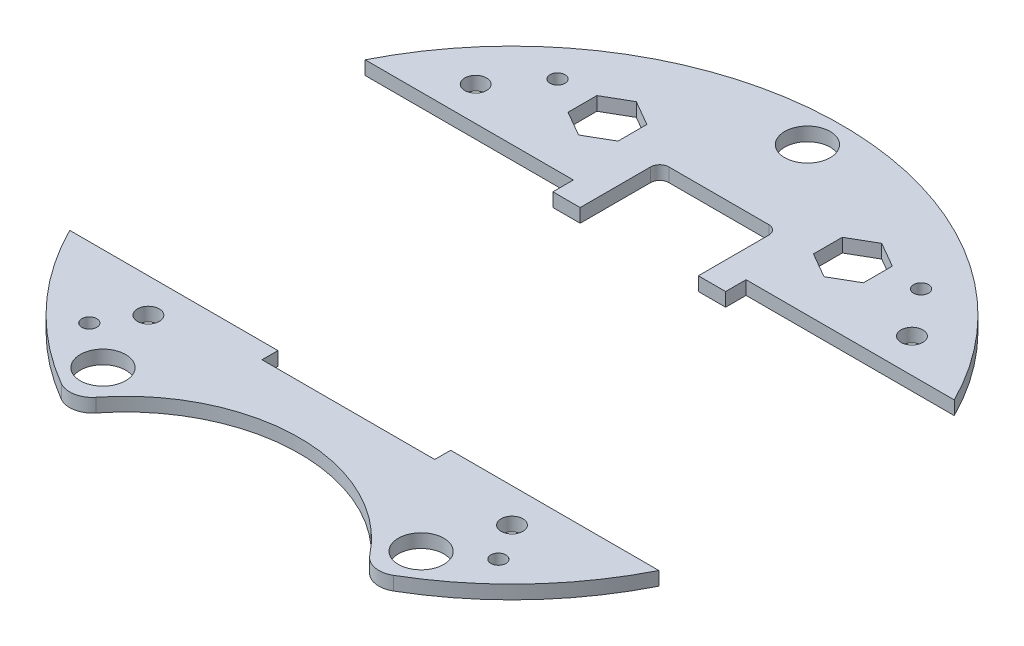
SolidWorks part; units mm, degrees
material "Acrylic (Medium-high impact)"
ref_plane "Front Plane" through (0, 0, 0) normal (0, 0, 1) x (1, 0, 0)
ref_plane "Top Plane" through (0, 0, 0) normal (0, 1, 0) x (1, 0, 0)
ref_plane "Right Plane" through (0, 0, 0) normal (1, 0, 0) x (0, 0, -1)
sketch "Sketch1" plane through (0, 0, 0) normal (0, 1, 0) x (1, 0, 0)
  line L0 (0, -85) -> (-32.4891, -64.8129) construction
  line L1 (0, -85) -> (0, 0) construction
  arc A0 (36.5434, -62.6165) -> (-36.5434, -62.6165) centre (0, 0) ccw
  arc A1 (30.0898, -61.3851) -> (-30.0898, -61.3851) centre (0, -85) ccw
  arc A2 (-30.0898, -61.3851) -> (-36.5434, -62.6165) centre (-34.0231, -58.2982) cw
  arc A3 (36.5434, -62.6165) -> (30.0898, -61.3851) centre (34.0231, -58.2982) cw
  dimension "D1" = 145
  dimension "D2" = 76.5
  dimension "D4" = 5
  dimension "D3" = 85
extrude "Boss-Extrude1" add sketch "Sketch1" along normal blind 3
sketch "solenoid placement" plane through (0, 3, 0) normal (0, 1, 0) x (1, 0, 0)
  line L4 (-19, -36) -> (19, -36)
  line L5 (-19, 28) -> (-19, -36)
  line L6 (19, 28) -> (-19, 28)
  line L7 (19, -36) -> (19, 28)
  line L8 (-19, -36) -> (19, -36)
  line L9 (-19, 28) -> (-19, -36)
  line L10 (19, 28) -> (-19, 28)
  line L11 (19, -36) -> (19, 28)
  dimension "D1" = 0
extrude "Cut-Extrude1" cut sketch "solenoid placement" against normal through all
sketch "Sketch4" plane through (0, 3, 0) normal (0, 1, 0) x (1, 0, 0)
  line L8 (13, 28) -> (13, 43.5)
  line L9 (-13, 28) -> (13, 28)
  line L10 (-13, 43.5) -> (-13, 28)
  line L11 (11, 45.5) -> (-11, 45.5)
  line L28 (13, 28) -> (13, 43.5)
  line L29 (-13, 28) -> (13, 28)
  line L30 (-13, 43.5) -> (-13, 28)
  line L31 (11, 45.5) -> (-11, 45.5)
  arc A4 (-11, 45.5) -> (-13, 43.5) centre (-11, 43.5) ccw
  arc A5 (13, 43.5) -> (11, 45.5) centre (11, 43.5) ccw
  arc A14 (-11, 45.5) -> (-13, 43.5) centre (-11, 43.5) ccw
  arc A15 (13, 43.5) -> (11, 45.5) centre (11, 43.5) ccw
  dimension "D1" = 0
extrude "Cut-Extrude4" cut sketch "Sketch4" against normal through all
sketch "Sketch5" plane through (0, 3, 0) normal (0, 1, 0) x (1, 0, 0)
  line L12 (-21.5, 51.1754) -> (-27, 54.3509)
  line L13 (-27, 54.3509) -> (-32.5, 51.1754)
  line L14 (-32.5, 51.1754) -> (-32.5, 44.8246)
  line L15 (-32.5, 44.8246) -> (-27, 41.6491)
  line L16 (-27, 41.6491) -> (-21.5, 44.8246)
  line L17 (-21.5, 44.8246) -> (-21.5, 51.1754)
  line L18 (-21.5, 51.1754) -> (-27, 54.3509)
  line L19 (-27, 54.3509) -> (-32.5, 51.1754)
  line L20 (-32.5, 51.1754) -> (-32.5, 44.8246)
  line L21 (-32.5, 44.8246) -> (-27, 41.6491)
  line L22 (-27, 41.6491) -> (-21.5, 44.8246)
  line L23 (-21.5, 44.8246) -> (-21.5, 51.1754)
  line L24 (21.5, 51.1754) -> (21.5, 44.8246)
  line L25 (21.5, 44.8246) -> (27, 41.6491)
  line L26 (27, 41.6491) -> (32.5, 44.8246)
  line L27 (32.5, 44.8246) -> (32.5, 51.1754)
  line L28 (32.5, 51.1754) -> (27, 54.3509)
  line L29 (27, 54.3509) -> (21.5, 51.1754)
  line L42 (21.5, 51.1754) -> (21.5, 44.8246)
  line L43 (21.5, 44.8246) -> (27, 41.6491)
  line L44 (27, 41.6491) -> (32.5, 44.8246)
  line L45 (32.5, 44.8246) -> (32.5, 51.1754)
  line L46 (32.5, 51.1754) -> (27, 54.3509)
  line L47 (27, 54.3509) -> (21.5, 51.1754)
  dimension "D1" = 0
  dimension "D2" = 0
extrude "Cut-Extrude5" cut sketch "Sketch5" against normal through all
sketch "Sketch6" plane through (0, 3, 0) normal (0, 1, 0) x (1, 0, 0)
  circle A1 centre (40, -40) radius 2.4
  circle A2 centre (40, -40) radius 2.4
  circle A3 centre (-40, -40) radius 2.4
  circle A4 centre (-40, -40) radius 2.4
  circle A5 centre (48, 40) radius 2.4
  circle A6 centre (48, 40) radius 2.4
  circle A7 centre (-48, 40) radius 2.4
  circle A8 centre (-48, 40) radius 2.4
  dimension "D1" = 0
  dimension "D2" = 0
  dimension "D3" = 0
  dimension "D4" = 0
extrude "Cut-Extrude6" cut sketch "Sketch6" against normal through all
sketch "Sketch3" plane through (0, 3, 0) normal (0, 1, 0) x (1, 0, 0)
  line L0 (-19, 28) -> (-19, 32.5)
  line L1 (72.5, -32.5) -> (-72.5, -32.5)
  line L2 (72.5, -32.5) -> (72.5, 32.5)
  line L3 (72.5, 32.5) -> (19, 32.5)
  line L4 (-72.5, -32.5) -> (-72.5, 32.5)
  line L5 (72.5, -32.5) -> (-72.5, 32.5) construction
  line L6 (72.5, 32.5) -> (-72.5, -32.5) construction
  line L7 (-19, 28) -> (19, 28)
  line L8 (19, 28) -> (19, 32.5)
  line L9 (-19, 32.5) -> (-72.5, 32.5)
  line L10 (-19, 28) -> (-19, -36) construction
  line L11 (-13, 28) -> (-19, 28) construction
  arc A0 (36.5434, -62.6165) -> (-36.5434, -62.6165) centre (0, 0) ccw construction
  point P0 (0, 0)
  dimension "D1" = 65
extrude "Cut-Extrude3" cut sketch "Sketch3" against normal through all
sketch "Sketch7" plane through (0, 3, 0) normal (0, 1, 0) x (1, 0, 0)
  circle A1 centre (35, -55) radius 5
  circle A2 centre (35, -55) radius 5
  circle A3 centre (-35, -55) radius 5
  circle A4 centre (-35, -55) radius 5
  dimension "D1" = 0
  dimension "D2" = 0
extrude "Cut-Extrude7" cut sketch "Sketch7" against normal through all
sketch "Sketch8" plane through (0, 3, 0) normal (0, -1, 0) x (1, 0, 0)
  circle A1 centre (0, -65) radius 5
  circle A2 centre (0, -65) radius 5
  dimension "D1" = 0
extrude "Cut-Extrude9" cut sketch "Sketch8" along normal through all
sketch "Sketch9" plane through (0, 3, 0) normal (0, 1, 0) x (1, 0, 0)
  line L0 (0, 0) -> (0, -21.5516) construction
  circle A0 centre (45, -48) radius 1.65
  circle A1 centre (-45, -48) radius 1.65
  circle A2 centre (40, 50) radius 1.65
  circle A3 centre (-40, 50) radius 1.65
  dimension "D3" = 3.3
  dimension "D1" = 45
  dimension "D2" = 48
  dimension "D4" = 40
  dimension "D5" = 50
extrude "Cut-Extrude10" cut sketch "Sketch9" against normal through all
equation "\"smallPulleyTeeth\"= 30"
equation "\"largePulleyTeeth\"= 30"
equation "\"eighthThick\"= 3.0mm"
equation "\"sixteenthThick\" = 1.7mm"
equation "\"quarterThick\"=6.0mm"
equation "\"OD\" = 145mm"
equation "\"puckAngle\" = 60.5deg"
equation "\"D1@Sketch1\"=\"OD\""
equation "\"puckDiam\" = 76.5mm"
equation "\"D2@Sketch1\"=\"puckDiam\""
equation "\"D1@Boss-Extrude1\"=\"eighthThick\""
equation "\"axlePress\" = 5.9mm"
equation "\"press\" = 0.2mm"
equation "\"wheelClear\" = 0.3mm"
equation "\"10-32clear\" = 4.8mm"
equation "\"6-32clear\" = 3.3mm"
equation "\"8-32clear\" = 4.0mm"
equation "\"wheelHeight\" = 22mm"
equation "\"wheelWell\" = 65mm"
equation "\"D1@Sketch3\"=\"wheelWell\""
equation "\"puckDist\" = 85mm"
equation "\"scoopFillet\" = 5mm"
equation "\"4-40clear\" = 3.0mm"
equation "\"D3@Sketch1\"=\"puckDist\""
equation "\"D4@Sketch1\"=\"scoopFillet\""
equation "\"D3@Sketch9\"=\"6-32clear\""
